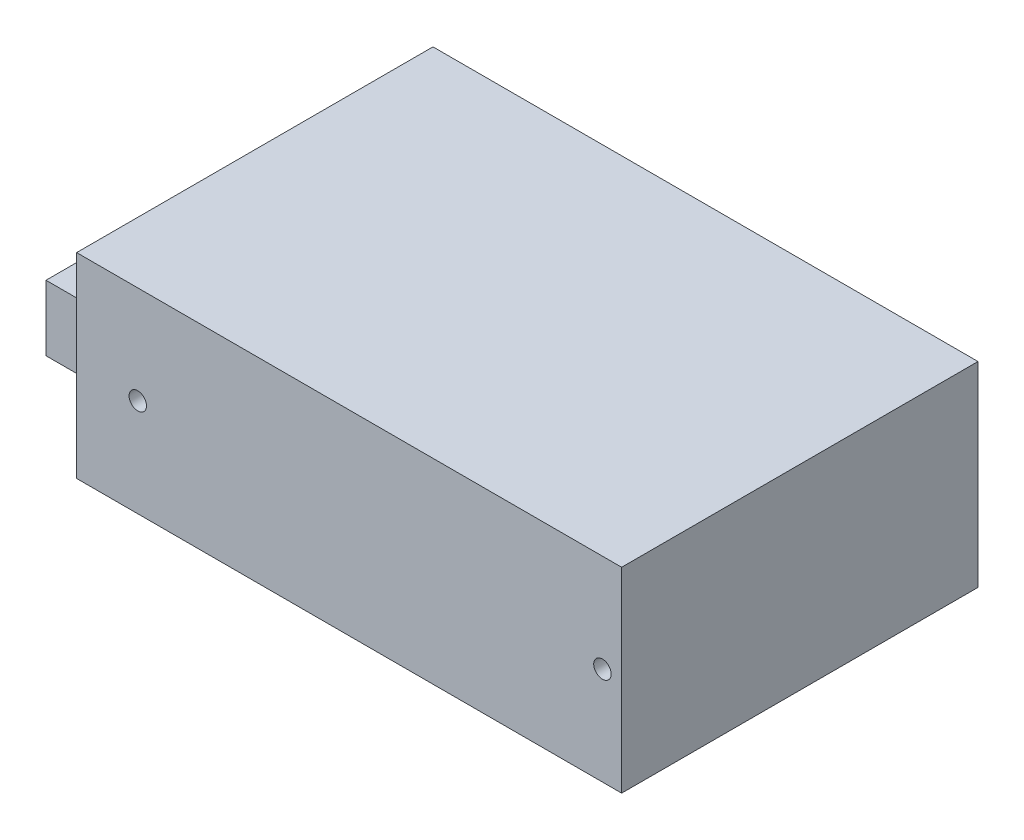
SolidWorks part; units mm, degrees
material "1060 Сплав"
ref_plane "Спереди" through (0, 0, 0) normal (0, 0, 1) x (1, 0, 0)
ref_plane "Сверху" through (0, 0, 0) normal (0, 1, 0) x (1, 0, 0)
ref_plane "Справа" through (0, 0, 0) normal (1, 0, 0) x (0, 0, -1)
sketch "Эскиз1" plane through (0, 0, 0) normal (0, 1, 0) x (1, 0, 0)
  line L1 (39, -25.5) -> (-39, -25.5)
  line L2 (39, -25.5) -> (39, 25.5)
  line L3 (39, 25.5) -> (-39, 25.5)
  line L4 (-39, -25.5) -> (-39, 25.5)
  line L5 (39, -25.5) -> (-39, 25.5) construction
  line L6 (39, 25.5) -> (-39, -25.5) construction
  point P0 (0, 0)
  dimension "D1" = 78
  dimension "D2" = 51
extrude "Бобышка-Вытянуть1" add sketch "Эскиз1" along normal blind 28
hole_wizard "Отверстие обработанное метчиком M31" positions "Эскиз2" profile "Эскиз3" tap size "M3" standard "ISO"
sketch "Эскиз2" plane through (0, 0, 25.5) normal (0, 0, 1) x (1, 0, 0)
  line L0 (-39, 0) -> (39, 0) construction
  line L1 (39, 28) -> (39, 0) construction
  point P0 (36.25, 14)
  point P2 (-30.25, 14)
  point P7 (0, 0)
  dimension "D1" = 14
  dimension "D2" = 2.75
  dimension "D3" = 66.5
sketch "Эскиз3" plane through (36.25, 14, 25.5) normal (1, 0, 0) x (0, -1, 0)
  line L0 (0, 0) -> (0, 6.2511)
  line L1 (0, 6.2511) -> (1.25, 5.5)
  line L2 (1.25, 5.5) -> (1.25, 0)
  line L5 (1.25, 0) -> (0, 0)
  line L10 (0, 6.2511) -> (-1.25, 5.5) construction
  line L11 (0, -6.35) -> (0, 107.95) construction
  dimension "Диаметр сверла" = 2.5
  dimension "Глубина сверла" = 5.5
  dimension "Угол заточки сверла" = 118
cosmetic thread "Отверстие резьбы1" parameters "D1"=3, "D2"=3
cosmetic thread "Отверстие резьбы2" parameters "D1"=3, "D2"=3
hole_wizard "Отверстие обработанное метчиком M32" positions "Эскиз4" profile "Эскиз5" tap size "M3" standard "ISO"
sketch "Эскиз4" plane through (0, 0, 0) normal (0, -1, 0) x (-1, 0, 0)
  line L1 (39, -25.5) -> (-39, -25.5) construction
  line L2 (-39, -25.5) -> (-39, 25.5) construction
  point P0 (-28, -0.1)
  point P2 (27, -0.1)
  point P9 (0, 0)
  dimension "D1" = 25.4
  dimension "D2" = 11
  dimension "D3" = 55
sketch "Эскиз5" plane through (28, 0, 0.1) normal (1, 0, 0) x (0, 0, -1)
  line L0 (0, 0) -> (0, 6.2511)
  line L1 (0, 6.2511) -> (1.25, 5.5)
  line L2 (1.25, 5.5) -> (1.25, 0)
  line L5 (1.25, 0) -> (0, 0)
  line L10 (0, 6.2511) -> (-1.25, 5.5) construction
  line L11 (0, -6.35) -> (0, 107.95) construction
  dimension "Диаметр сверла" = 2.5
  dimension "Глубина сверла" = 5.5
  dimension "Угол заточки сверла" = 118
cosmetic thread "Отверстие резьбы3" parameters "D1"=3, "D2"=3
cosmetic thread "Отверстие резьбы4" parameters "D1"=3, "D2"=3
sketch "Эскиз6" plane through (-39, 0, 0) normal (-1, 0, 0) x (0, 0, 1)
  line L1 (-20.6708, 3.4016) -> (15.8844, 3.4016)
  line L2 (-20.6708, 3.4016) -> (-20.6708, 12.764)
  line L3 (-20.6708, 12.764) -> (15.8844, 12.764)
  line L4 (15.8844, 3.4016) -> (15.8844, 12.764)
  line L5 (-2.3932, 12.764) -> (-2.3932, 3.4016) construction
  line L6 (-20.6708, 8.0828) -> (15.8844, 8.0828) construction
  point P220 (-2.3932, 8.0828)
extrude "Бобышка-Вытянуть2" add sketch "Эскиз6" along normal blind 14
